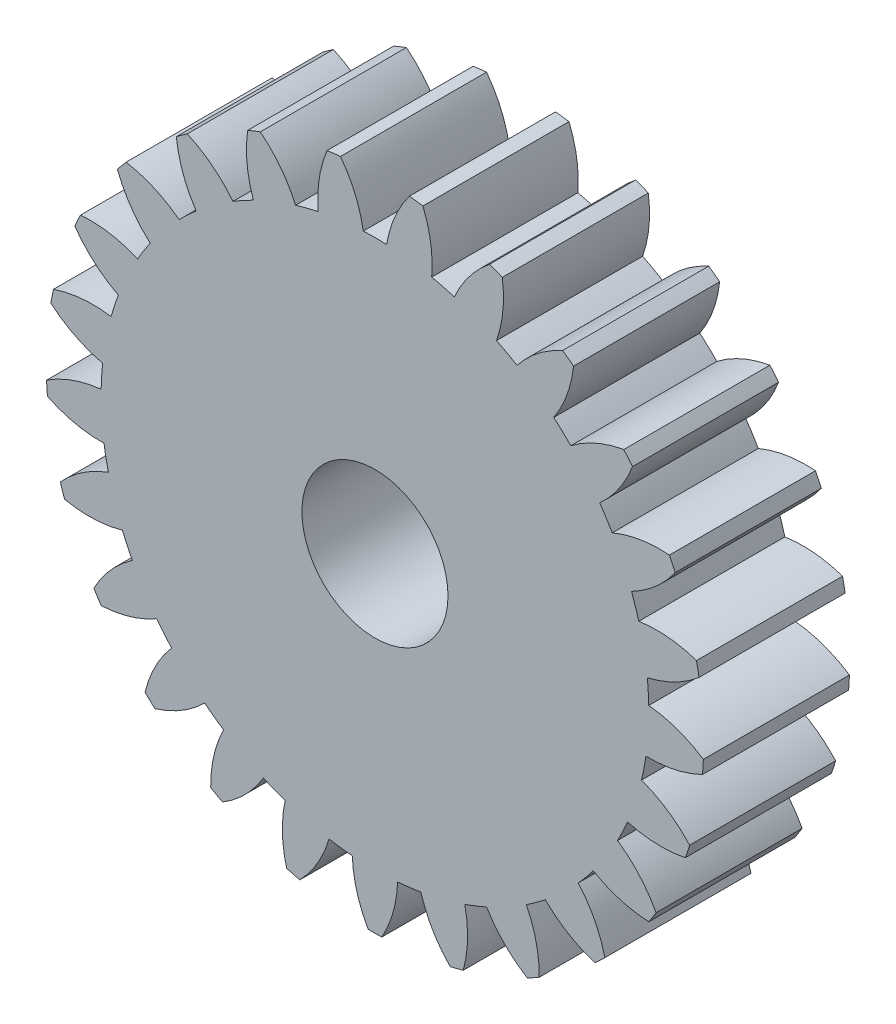
SolidWorks part; units mm, degrees
ref_plane "前视基准面" through (0, 0, 0) normal (0, 0, 1) x (1, 0, 0)
ref_plane "上视基准面" through (0, 0, 0) normal (0, 1, 0) x (1, 0, 0)
ref_plane "右视基准面" through (0, 0, 0) normal (1, 0, 0) x (0, 0, -1)
sketch "草图1" plane through (0, 0, 0) normal (0, 0, 1) x (1, 0, 0)
  circle A0 centre (0, 0) radius 1.5 construction
  circle A1 centre (0, 0) radius 1.5
  arc A100 (-6.6552, 1.1273) -> (-5.5927, 0.5923) centre (-5.032, 3.0286) ccw
  arc A101 (-5.5927, 0.5923) -> (-5.6229, 0.1133) centre (0, 0) ccw
  arc A102 (-5.6229, 0.1133) -> (-6.744, -0.2843) centre (-5.3719, -2.374) ccw
  arc A103 (-6.744, -0.2843) -> (-6.7265, -0.5632) centre (0, 0) ccw
  arc A104 (-6.7265, -0.5632) -> (-5.5643, -0.8172) centre (-5.6271, 1.6821) ccw
  arc A105 (-5.5643, -0.8172) -> (-5.4744, -1.2886) centre (0, 0) ccw
  arc A106 (-5.4744, -1.2886) -> (-6.4614, -1.9525) centre (-4.6127, -3.6354) ccw
  arc A107 (-6.4614, -1.9525) -> (-6.3751, -2.2183) centre (0, 0) ccw
  arc A108 (-6.3751, -2.2183) -> (-5.1863, -2.1753) centre (-5.8686, 0.2298) ccw
  arc A109 (-5.1863, -2.1753) -> (-4.9819, -2.6095) centre (0, 0) ccw
  arc A110 (-4.9819, -2.6095) -> (-5.7729, -3.498) centre (-3.5637, -4.6683) ccw
  arc A111 (-5.7729, -3.498) -> (-5.6231, -3.7341) centre (0, 0) ccw
  arc A112 (-5.6231, -3.7341) -> (-4.4824, -3.3967) centre (-5.7414, -1.2369) ccw
  arc A113 (-4.4824, -3.3967) -> (-4.1765, -3.7665) centre (0, 0) ccw
  arc A114 (-4.1765, -3.7665) -> (-4.7216, -4.8238) centre (-2.2908, -5.4079) ccw
  arc A115 (-4.7216, -4.8238) -> (-4.5178, -5.0152) centre (0, 0) ccw
  arc A116 (-4.5178, -5.0152) -> (-3.4968, -4.4047) centre (-5.2534, -2.6258) ccw
  arc A117 (-3.4968, -4.4047) -> (-3.1086, -4.6868) centre (0, 0) ccw
  arc A118 (-3.1086, -4.6868) -> (-3.3736, -5.8465) centre (-0.8739, -5.8077) ccw
  arc A119 (-3.3736, -5.8465) -> (-3.1287, -5.9811) centre (0, 0) ccw
  arc A120 (-3.1287, -5.9811) -> (-2.2916, -5.136) centre (-4.4353, -3.8498) ccw
  arc A121 (-2.2916, -5.136) -> (-1.8453, -5.3126) centre (0, 0) ccw
  arc A122 (-1.8453, -5.3126) -> (-1.8137, -6.5018) centre (0.5979, -5.8426) ccw
  arc A123 (-1.8137, -6.5018) -> (-1.5429, -6.5713) centre (0, 0) ccw
  arc A124 (-1.5429, -6.5713) -> (-0.9423, -5.5445) centre (-3.3386, -4.8319) ccw
  arc A125 (-0.9423, -5.5445) -> (-0.4662, -5.6046) centre (0, 0) ccw
  arc A126 (-0.4662, -5.6046) -> (-0.1398, -6.7486) centre (2.0321, -5.5103) ccw
  arc A127 (-0.1398, -6.7486) -> (0.1398, -6.7486) centre (0, 0) ccw
  arc A128 (0.1398, -6.7486) -> (0.4662, -5.6046) centre (-2.0321, -5.5103) ccw
  arc A129 (0.4662, -5.6046) -> (0.9423, -5.5445) centre (0, 0) ccw
  arc A130 (0.9423, -5.5445) -> (1.5429, -6.5713) centre (3.3386, -4.8319) ccw
  arc A131 (1.5429, -6.5713) -> (1.8137, -6.5018) centre (0, 0) ccw
  arc A132 (1.8137, -6.5018) -> (1.8453, -5.3126) centre (-0.5979, -5.8426) ccw
  arc A133 (1.8453, -5.3126) -> (2.2916, -5.136) centre (0, 0) ccw
  arc A134 (2.2916, -5.136) -> (3.1287, -5.9811) centre (4.4353, -3.8498) ccw
  arc A135 (3.1287, -5.9811) -> (3.3736, -5.8465) centre (0, 0) ccw
  arc A136 (3.3736, -5.8465) -> (3.1086, -4.6868) centre (0.8739, -5.8077) ccw
  arc A137 (3.1086, -4.6868) -> (3.4968, -4.4047) centre (0, 0) ccw
  arc A138 (3.4968, -4.4047) -> (4.5178, -5.0152) centre (5.2534, -2.6258) ccw
  arc A139 (4.5178, -5.0152) -> (4.7216, -4.8238) centre (0, 0) ccw
  arc A140 (4.7216, -4.8238) -> (4.1765, -3.7665) centre (2.2908, -5.4079) ccw
  arc A141 (4.1765, -3.7665) -> (4.4824, -3.3967) centre (0, 0) ccw
  arc A142 (4.4824, -3.3967) -> (5.6231, -3.7341) centre (5.7414, -1.2369) ccw
  arc A143 (5.6231, -3.7341) -> (5.7729, -3.498) centre (0, 0) ccw
  arc A144 (5.7729, -3.498) -> (4.9819, -2.6095) centre (3.5637, -4.6683) ccw
  arc A145 (4.9819, -2.6095) -> (5.1863, -2.1753) centre (0, 0) ccw
  arc A146 (5.1863, -2.1753) -> (6.3751, -2.2183) centre (5.8686, 0.2298) ccw
  arc A147 (6.3751, -2.2183) -> (6.4614, -1.9525) centre (0, 0) ccw
  arc A148 (6.4614, -1.9525) -> (5.4744, -1.2886) centre (4.6127, -3.6354) ccw
  arc A149 (5.4744, -1.2886) -> (5.5643, -0.8172) centre (0, 0) ccw
  arc A150 (5.5643, -0.8172) -> (6.7265, -0.5632) centre (5.6271, 1.6821) ccw
  arc A151 (6.7265, -0.5632) -> (6.744, -0.2843) centre (0, 0) ccw
  arc A152 (6.744, -0.2843) -> (5.6229, 0.1133) centre (5.3719, -2.374) ccw
  arc A153 (5.6229, 0.1133) -> (5.5927, 0.5923) centre (0, 0) ccw
  arc A154 (5.5927, 0.5923) -> (6.6552, 1.1273) centre (5.032, 3.0286) ccw
  arc A155 (6.6552, 1.1273) -> (6.6028, 1.4018) centre (0, 0) ccw
  arc A156 (6.6028, 1.4018) -> (5.418, 1.5081) centre (5.7935, -0.9635) ccw
  arc A157 (5.418, 1.5081) -> (5.2697, 1.9645) centre (0, 0) ccw
  arc A158 (5.2697, 1.9645) -> (6.1658, 2.7469) centre (4.1207, 4.1848) ccw
  arc A159 (6.1658, 2.7469) -> (6.0468, 2.9999) centre (0, 0) ccw
  arc A160 (6.0468, 2.9999) -> (4.8728, 2.8081) centre (5.8511, 0.5075) ccw
  arc A161 (4.8728, 2.8081) -> (4.6156, 3.2134) centre (0, 0) ccw
  arc A162 (4.6156, 3.2134) -> (5.2889, 4.194) centre (2.9505, 5.0781) ccw
  arc A163 (5.2889, 4.194) -> (5.1108, 4.4094) centre (0, 0) ccw
  arc A164 (5.1108, 4.4094) -> (4.0213, 3.9317) centre (5.5411, 1.9467) ccw
  arc A165 (4.0213, 3.9317) -> (3.6715, 4.2603) centre (0, 0) ccw
  arc A166 (3.6715, 4.2603) -> (4.0798, 5.3775) centre (1.5949, 5.6524) ccw
  arc A167 (4.0798, 5.3775) -> (3.8536, 5.5418) centre (0, 0) ccw
  arc A168 (3.8536, 5.5418) -> (2.9172, 4.8083) centre (4.8829, 3.2635) ccw
  arc A169 (2.9172, 4.8083) -> (2.4966, 5.0395) centre (0, 0) ccw
  arc A170 (2.4966, 5.0395) -> (2.6143, 6.2232) centre (0.1391, 5.8714) ccw
  arc A171 (2.6143, 6.2232) -> (2.3544, 6.3261) centre (0, 0) ccw
  arc A172 (2.3544, 6.3261) -> (1.6298, 5.3827) centre (3.9178, 4.3753) ccw
  arc A173 (1.6298, 5.3827) -> (1.1649, 5.502) centre (0, 0) ccw
  arc A174 (1.1649, 5.502) -> (0.9845, 6.6778) centre (-1.3254, 5.7216) ccw
  arc A175 (0.9845, 6.6778) -> (0.7072, 6.7129) centre (0, 0) ccw
  arc A176 (0.7072, 6.7129) -> (0.24, 5.6189) centre (2.7067, 5.2122) ccw
  arc A177 (0.24, 5.6189) -> (-0.24, 5.6189) centre (0, 0) ccw
  arc A178 (-0.24, 5.6189) -> (-0.7072, 6.7129) centre (-2.7067, 5.2122) ccw
  arc A179 (-0.7072, 6.7129) -> (-0.9845, 6.6778) centre (0, 0) ccw
  arc A180 (-0.9845, 6.6778) -> (-1.1649, 5.502) centre (1.3254, 5.7216) ccw
  arc A181 (-1.1649, 5.502) -> (-1.6298, 5.3827) centre (0, 0) ccw
  arc A182 (-1.6298, 5.3827) -> (-2.3544, 6.3261) centre (-3.9178, 4.3753) ccw
  arc A183 (-2.3544, 6.3261) -> (-2.6143, 6.2232) centre (0, 0) ccw
  arc A184 (-2.6143, 6.2232) -> (-2.4966, 5.0395) centre (-0.1391, 5.8714) ccw
  arc A185 (-2.4966, 5.0395) -> (-2.9172, 4.8083) centre (0, 0) ccw
  arc A186 (-2.9172, 4.8083) -> (-3.8536, 5.5418) centre (-4.8829, 3.2635) ccw
  arc A187 (-3.8536, 5.5418) -> (-4.0798, 5.3775) centre (0, 0) ccw
  arc A188 (-4.0798, 5.3775) -> (-3.6715, 4.2603) centre (-1.5949, 5.6524) ccw
  arc A189 (-3.6715, 4.2603) -> (-4.0213, 3.9317) centre (0, 0) ccw
  arc A190 (-4.0213, 3.9317) -> (-5.1108, 4.4094) centre (-5.5411, 1.9467) ccw
  arc A191 (-5.1108, 4.4094) -> (-5.2889, 4.194) centre (0, 0) ccw
  arc A192 (-5.2889, 4.194) -> (-4.6156, 3.2134) centre (-2.9505, 5.0781) ccw
  arc A193 (-4.6156, 3.2134) -> (-4.8728, 2.8081) centre (0, 0) ccw
  arc A194 (-4.8728, 2.8081) -> (-6.0468, 2.9999) centre (-5.8511, 0.5075) ccw
  arc A195 (-6.0468, 2.9999) -> (-6.1658, 2.7469) centre (0, 0) ccw
  arc A196 (-6.1658, 2.7469) -> (-5.2697, 1.9645) centre (-4.1207, 4.1848) ccw
  arc A197 (-5.2697, 1.9645) -> (-5.418, 1.5081) centre (0, 0) ccw
  arc A198 (-5.418, 1.5081) -> (-6.6028, 1.4018) centre (-5.7935, -0.9635) ccw
  arc A199 (-6.6028, 1.4018) -> (-6.6552, 1.1273) centre (0, 0) ccw
  arc A200 (-6.6552, 1.1273) -> (-5.5927, 0.5923) centre (-5.032, 3.0286) ccw
  arc A201 (-5.5927, 0.5923) -> (-5.6229, 0.1133) centre (0, 0) ccw
  arc A202 (-5.6229, 0.1133) -> (-6.744, -0.2843) centre (-5.3719, -2.374) ccw
  arc A203 (-6.744, -0.2843) -> (-6.7265, -0.5632) centre (0, 0) ccw
  arc A204 (-6.7265, -0.5632) -> (-5.5643, -0.8172) centre (-5.6271, 1.6821) ccw
  arc A205 (-5.5643, -0.8172) -> (-5.4744, -1.2886) centre (0, 0) ccw
  arc A206 (-5.4744, -1.2886) -> (-6.4614, -1.9525) centre (-4.6127, -3.6354) ccw
  arc A207 (-6.4614, -1.9525) -> (-6.3751, -2.2183) centre (0, 0) ccw
  arc A208 (-6.3751, -2.2183) -> (-5.1863, -2.1753) centre (-5.8686, 0.2298) ccw
  arc A209 (-5.1863, -2.1753) -> (-4.9819, -2.6095) centre (0, 0) ccw
  arc A210 (-4.9819, -2.6095) -> (-5.7729, -3.498) centre (-3.5637, -4.6683) ccw
  arc A211 (-5.7729, -3.498) -> (-5.6231, -3.7341) centre (0, 0) ccw
  arc A212 (-5.6231, -3.7341) -> (-4.4824, -3.3967) centre (-5.7414, -1.2369) ccw
  arc A213 (-4.4824, -3.3967) -> (-4.1765, -3.7665) centre (0, 0) ccw
  arc A214 (-4.1765, -3.7665) -> (-4.7216, -4.8238) centre (-2.2908, -5.4079) ccw
  arc A215 (-4.7216, -4.8238) -> (-4.5178, -5.0152) centre (0, 0) ccw
  arc A216 (-4.5178, -5.0152) -> (-3.4968, -4.4047) centre (-5.2534, -2.6258) ccw
  arc A217 (-3.4968, -4.4047) -> (-3.1086, -4.6868) centre (0, 0) ccw
  arc A218 (-3.1086, -4.6868) -> (-3.3736, -5.8465) centre (-0.8739, -5.8077) ccw
  arc A219 (-3.3736, -5.8465) -> (-3.1287, -5.9811) centre (0, 0) ccw
  arc A220 (-3.1287, -5.9811) -> (-2.2916, -5.136) centre (-4.4353, -3.8498) ccw
  arc A221 (-2.2916, -5.136) -> (-1.8453, -5.3126) centre (0, 0) ccw
  arc A222 (-1.8453, -5.3126) -> (-1.8137, -6.5018) centre (0.5979, -5.8426) ccw
  arc A223 (-1.8137, -6.5018) -> (-1.5429, -6.5713) centre (0, 0) ccw
  arc A224 (-1.5429, -6.5713) -> (-0.9423, -5.5445) centre (-3.3386, -4.8319) ccw
  arc A225 (-0.9423, -5.5445) -> (-0.4662, -5.6046) centre (0, 0) ccw
  arc A226 (-0.4662, -5.6046) -> (-0.1398, -6.7486) centre (2.0321, -5.5103) ccw
  arc A227 (-0.1398, -6.7486) -> (0.1398, -6.7486) centre (0, 0) ccw
  arc A228 (0.1398, -6.7486) -> (0.4662, -5.6046) centre (-2.0321, -5.5103) ccw
  arc A229 (0.4662, -5.6046) -> (0.9423, -5.5445) centre (0, 0) ccw
  arc A230 (0.9423, -5.5445) -> (1.5429, -6.5713) centre (3.3386, -4.8319) ccw
  arc A231 (1.5429, -6.5713) -> (1.8137, -6.5018) centre (0, 0) ccw
  arc A232 (1.8137, -6.5018) -> (1.8453, -5.3126) centre (-0.5979, -5.8426) ccw
  arc A233 (1.8453, -5.3126) -> (2.2916, -5.136) centre (0, 0) ccw
  arc A234 (2.2916, -5.136) -> (3.1287, -5.9811) centre (4.4353, -3.8498) ccw
  arc A235 (3.1287, -5.9811) -> (3.3736, -5.8465) centre (0, 0) ccw
  arc A236 (3.3736, -5.8465) -> (3.1086, -4.6868) centre (0.8739, -5.8077) ccw
  arc A237 (3.1086, -4.6868) -> (3.4968, -4.4047) centre (0, 0) ccw
  arc A238 (3.4968, -4.4047) -> (4.5178, -5.0152) centre (5.2534, -2.6258) ccw
  arc A239 (4.5178, -5.0152) -> (4.7216, -4.8238) centre (0, 0) ccw
  arc A240 (4.7216, -4.8238) -> (4.1765, -3.7665) centre (2.2908, -5.4079) ccw
  arc A241 (4.1765, -3.7665) -> (4.4824, -3.3967) centre (0, 0) ccw
  arc A242 (4.4824, -3.3967) -> (5.6231, -3.7341) centre (5.7414, -1.2369) ccw
  arc A243 (5.6231, -3.7341) -> (5.7729, -3.498) centre (0, 0) ccw
  arc A244 (5.7729, -3.498) -> (4.9819, -2.6095) centre (3.5637, -4.6683) ccw
  arc A245 (4.9819, -2.6095) -> (5.1863, -2.1753) centre (0, 0) ccw
  arc A246 (5.1863, -2.1753) -> (6.3751, -2.2183) centre (5.8686, 0.2298) ccw
  arc A247 (6.3751, -2.2183) -> (6.4614, -1.9525) centre (0, 0) ccw
  arc A248 (6.4614, -1.9525) -> (5.4744, -1.2886) centre (4.6127, -3.6354) ccw
  arc A249 (5.4744, -1.2886) -> (5.5643, -0.8172) centre (0, 0) ccw
  arc A250 (5.5643, -0.8172) -> (6.7265, -0.5632) centre (5.6271, 1.6821) ccw
  arc A251 (6.7265, -0.5632) -> (6.744, -0.2843) centre (0, 0) ccw
  arc A252 (6.744, -0.2843) -> (5.6229, 0.1133) centre (5.3719, -2.374) ccw
  arc A253 (5.6229, 0.1133) -> (5.5927, 0.5923) centre (0, 0) ccw
  arc A254 (5.5927, 0.5923) -> (6.6552, 1.1273) centre (5.032, 3.0286) ccw
  arc A255 (6.6552, 1.1273) -> (6.6028, 1.4018) centre (0, 0) ccw
  arc A256 (6.6028, 1.4018) -> (5.418, 1.5081) centre (5.7935, -0.9635) ccw
  arc A257 (5.418, 1.5081) -> (5.2697, 1.9645) centre (0, 0) ccw
  arc A258 (5.2697, 1.9645) -> (6.1658, 2.7469) centre (4.1207, 4.1848) ccw
  arc A259 (6.1658, 2.7469) -> (6.0468, 2.9999) centre (0, 0) ccw
  arc A260 (6.0468, 2.9999) -> (4.8728, 2.8081) centre (5.8511, 0.5075) ccw
  arc A261 (4.8728, 2.8081) -> (4.6156, 3.2134) centre (0, 0) ccw
  arc A262 (4.6156, 3.2134) -> (5.2889, 4.194) centre (2.9505, 5.0781) ccw
  arc A263 (5.2889, 4.194) -> (5.1108, 4.4094) centre (0, 0) ccw
  arc A264 (5.1108, 4.4094) -> (4.0213, 3.9317) centre (5.5411, 1.9467) ccw
  arc A265 (4.0213, 3.9317) -> (3.6715, 4.2603) centre (0, 0) ccw
  arc A266 (3.6715, 4.2603) -> (4.0798, 5.3775) centre (1.5949, 5.6524) ccw
  arc A267 (4.0798, 5.3775) -> (3.8536, 5.5418) centre (0, 0) ccw
  arc A268 (3.8536, 5.5418) -> (2.9172, 4.8083) centre (4.8829, 3.2635) ccw
  arc A269 (2.9172, 4.8083) -> (2.4966, 5.0395) centre (0, 0) ccw
  arc A270 (2.4966, 5.0395) -> (2.6143, 6.2232) centre (0.1391, 5.8714) ccw
  arc A271 (2.6143, 6.2232) -> (2.3544, 6.3261) centre (0, 0) ccw
  arc A272 (2.3544, 6.3261) -> (1.6298, 5.3827) centre (3.9178, 4.3753) ccw
  arc A273 (1.6298, 5.3827) -> (1.1649, 5.502) centre (0, 0) ccw
  arc A274 (1.1649, 5.502) -> (0.9845, 6.6778) centre (-1.3254, 5.7216) ccw
  arc A275 (0.9845, 6.6778) -> (0.7072, 6.7129) centre (0, 0) ccw
  arc A276 (0.7072, 6.7129) -> (0.24, 5.6189) centre (2.7067, 5.2122) ccw
  arc A277 (0.24, 5.6189) -> (-0.24, 5.6189) centre (0, 0) ccw
  arc A278 (-0.24, 5.6189) -> (-0.7072, 6.7129) centre (-2.7067, 5.2122) ccw
  arc A279 (-0.7072, 6.7129) -> (-0.9845, 6.6778) centre (0, 0) ccw
  arc A280 (-0.9845, 6.6778) -> (-1.1649, 5.502) centre (1.3254, 5.7216) ccw
  arc A281 (-1.1649, 5.502) -> (-1.6298, 5.3827) centre (0, 0) ccw
  arc A282 (-1.6298, 5.3827) -> (-2.3544, 6.3261) centre (-3.9178, 4.3753) ccw
  arc A283 (-2.3544, 6.3261) -> (-2.6143, 6.2232) centre (0, 0) ccw
  arc A284 (-2.6143, 6.2232) -> (-2.4966, 5.0395) centre (-0.1391, 5.8714) ccw
  arc A285 (-2.4966, 5.0395) -> (-2.9172, 4.8083) centre (0, 0) ccw
  arc A286 (-2.9172, 4.8083) -> (-3.8536, 5.5418) centre (-4.8829, 3.2635) ccw
  arc A287 (-3.8536, 5.5418) -> (-4.0798, 5.3775) centre (0, 0) ccw
  arc A288 (-4.0798, 5.3775) -> (-3.6715, 4.2603) centre (-1.5949, 5.6524) ccw
  arc A289 (-3.6715, 4.2603) -> (-4.0213, 3.9317) centre (0, 0) ccw
  arc A290 (-4.0213, 3.9317) -> (-5.1108, 4.4094) centre (-5.5411, 1.9467) ccw
  arc A291 (-5.1108, 4.4094) -> (-5.2889, 4.194) centre (0, 0) ccw
  arc A292 (-5.2889, 4.194) -> (-4.6156, 3.2134) centre (-2.9505, 5.0781) ccw
  arc A293 (-4.6156, 3.2134) -> (-4.8728, 2.8081) centre (0, 0) ccw
  arc A294 (-4.8728, 2.8081) -> (-6.0468, 2.9999) centre (-5.8511, 0.5075) ccw
  arc A295 (-6.0468, 2.9999) -> (-6.1658, 2.7469) centre (0, 0) ccw
  arc A296 (-6.1658, 2.7469) -> (-5.2697, 1.9645) centre (-4.1207, 4.1848) ccw
  arc A297 (-5.2697, 1.9645) -> (-5.418, 1.5081) centre (0, 0) ccw
  arc A298 (-5.418, 1.5081) -> (-6.6028, 1.4018) centre (-5.7935, -0.9635) ccw
  arc A299 (-6.6028, 1.4018) -> (-6.6552, 1.1273) centre (0, 0) ccw
  dimension "D1" = 0
extrude "凸台-拉伸1" add sketch "草图1" along normal blind 3
